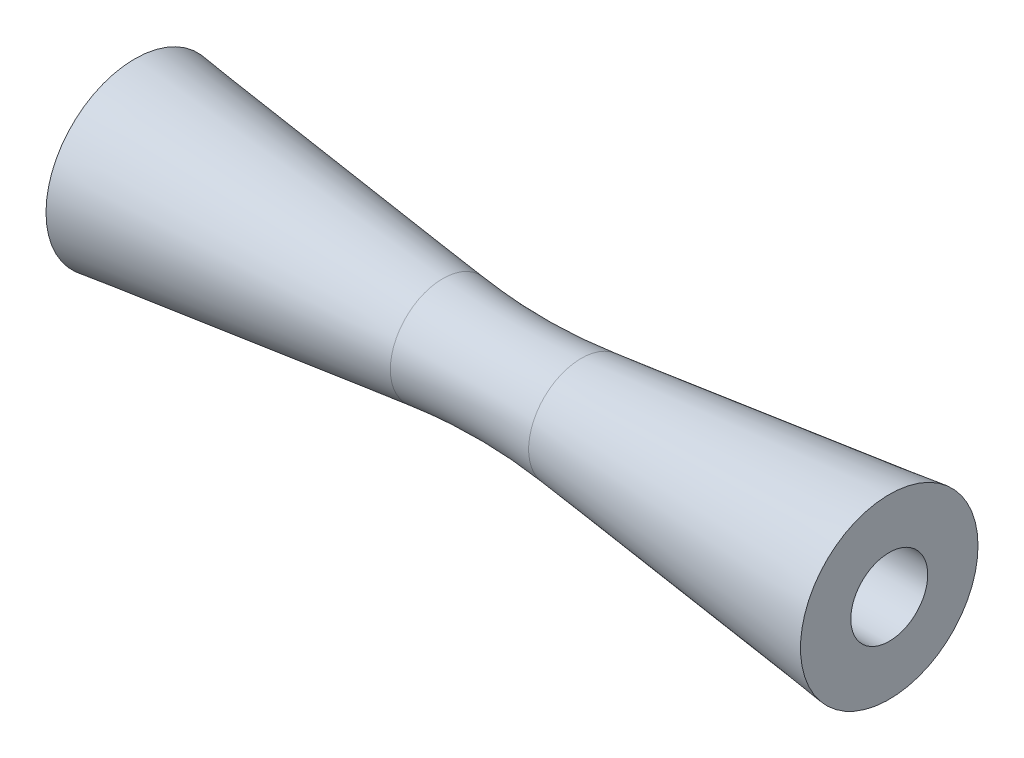
SolidWorks part; units mm, degrees
ref_plane "Front Plane" through (0, 0, 0) normal (0, 0, 1) x (1, 0, 0)
ref_plane "Top Plane" through (0, 0, 0) normal (0, 1, 0) x (1, 0, 0)
ref_plane "Right Plane" through (0, 0, 0) normal (1, 0, 0) x (0, 0, -1)
sketch "Sketch1" plane through (0, 0, 0) normal (0, 0, 1) x (1, 0, 0)
  line L0 (0, 0) -> (0, 7.62) construction
  line L1 (0, 7.62) -> (32.385, 3.81)
  line L2 (32.385, 3.81) -> (64.77, 7.62)
  line L3 (64.77, 7.62) -> (64.77, 0) construction
  line L4 (64.77, 0) -> (0, 0) construction
  line L5 (64.77, 3.302) -> (0, 3.302)
  line L6 (0, 7.62) -> (0, 3.302)
  line L7 (64.77, 7.62) -> (64.77, 3.302)
  dimension "D1" = 3.81
  dimension "D2" = 7.62
  dimension "D3" = 64.77
  dimension "D4" = 3.302
revolve "Revolve1" add sketch "Sketch1" angle 360 about L4
fillet "Fillet1" radius 50.8 1 edges at (32.385, 0, -3.81)
